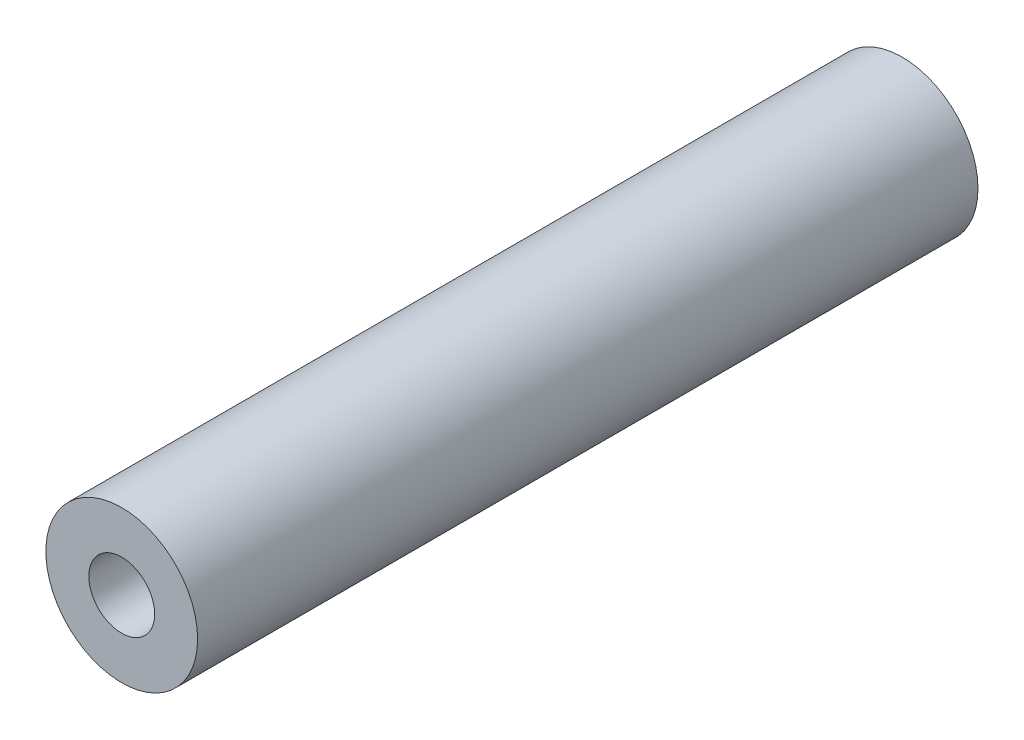
SolidWorks part; units mm, degrees
ref_plane "前视基准面" through (0, 0, 0) normal (0, 0, 1) x (1, 0, 0)
ref_plane "上视基准面" through (0, 0, 0) normal (0, 1, 0) x (1, 0, 0)
ref_plane "右视基准面" through (0, 0, 0) normal (1, 0, 0) x (0, 0, -1)
other "Configuration Table"
sketch "Sketch_36mm_post" plane through (0, 0, 0) normal (0, 0, 1) x (1, 0, 0)
  circle A0 centre (0, 0) radius 3.5
  dimension "D1" = 7
extrude "36mm_post" add sketch "Sketch_36mm_post" along normal blind 36 from offset 0
sketch "Sketch_M3_nominal_thread_envelope" plane through (0, 0, 0) normal (0, 0, 1) x (1, 0, 0)
  circle A0 centre (0, 0) radius 1.52
  dimension "D1" = 3.04
extrude "M3_nominal_thread_envelope" cut sketch "Sketch_M3_nominal_thread_envelope" along normal blind 38 from offset 1
